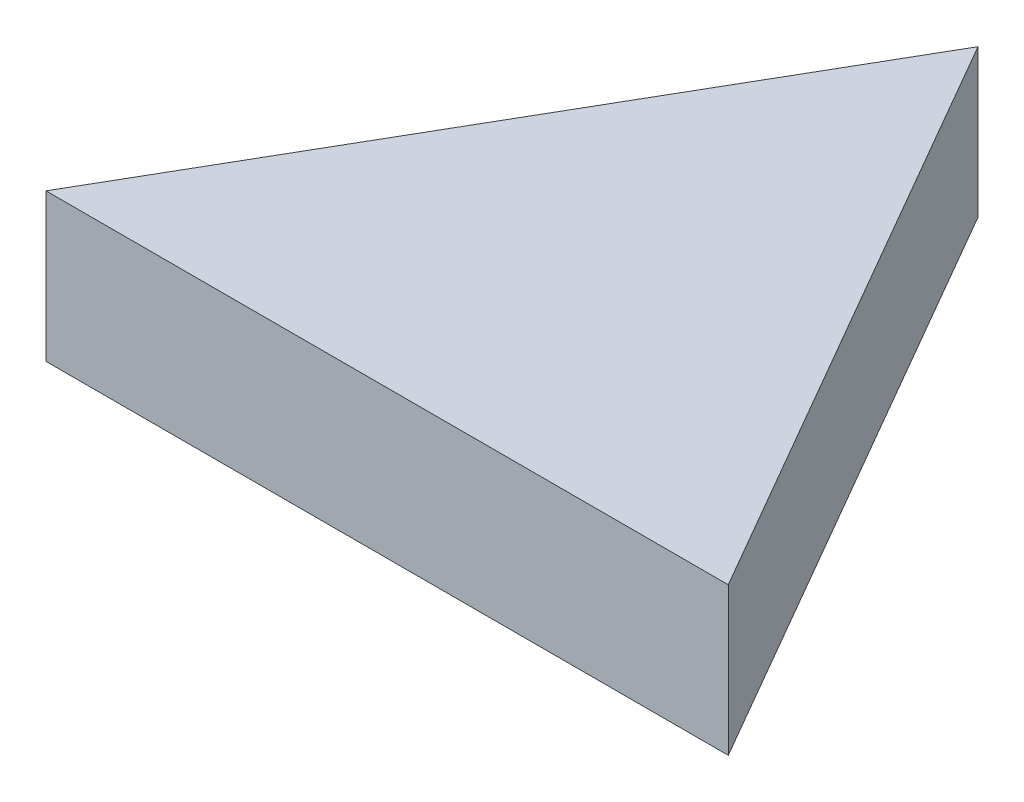
SolidWorks part; units mm, degrees
ref_plane "Front Plane" through (0, 0, 0) normal (0, 0, 1) x (1, 0, 0)
ref_plane "Top Plane" through (0, 0, 0) normal (0, 1, 0) x (1, 0, 0)
ref_plane "Right Plane" through (0, 0, 0) normal (1, 0, 0) x (0, 0, -1)
sketch "Sketch1" plane through (0, 0, 0) normal (0, 1, 0) x (1, 0, 0)
  line L1 (0, 16.9333) -> (-14.6647, -8.4667)
  line L2 (-14.6647, -8.4667) -> (14.6647, -8.4667)
  line L3 (14.6647, -8.4667) -> (0, 16.9333)
  circle A0 centre (0, 0) radius 8.4667 construction
  dimension "D1" = 25.4
extrude "Boss-Extrude1" add sketch "Sketch1" along normal blind 6.35
